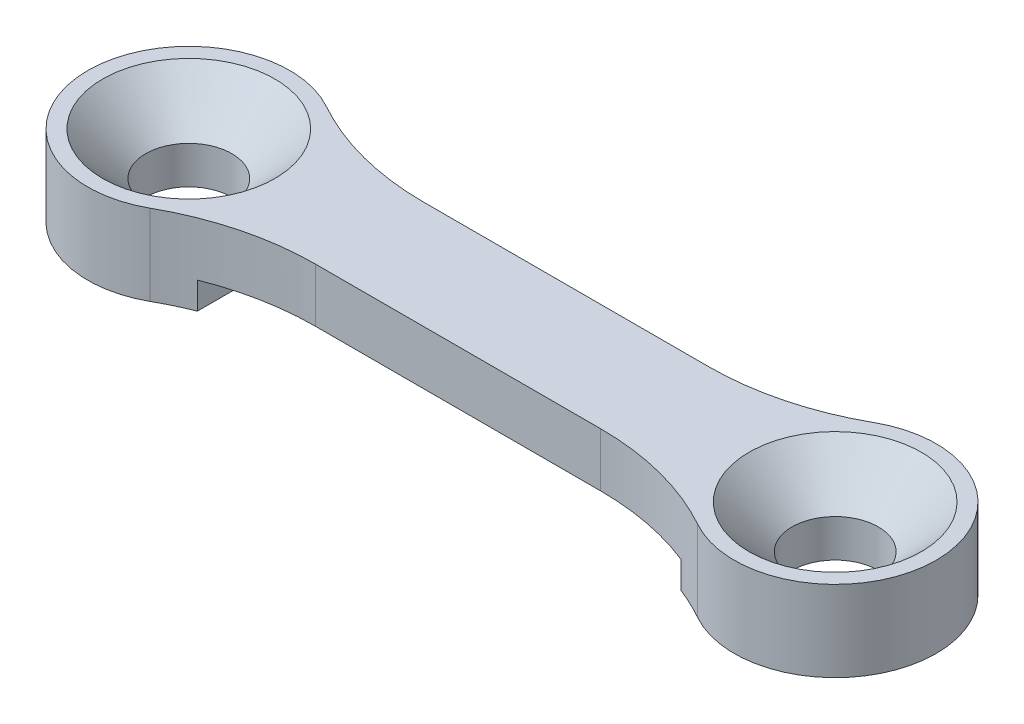
SolidWorks part; units mm, degrees
ref_plane "Front Plane" through (0, 0, 0) normal (0, 0, 1) x (1, 0, 0)
ref_plane "Top Plane" through (0, 0, 0) normal (0, 1, 0) x (1, 0, 0)
ref_plane "Right Plane" through (0, 0, 0) normal (1, 0, 0) x (0, 0, -1)
sketch "Sketch1" plane through (0, 0, 0) normal (0, 1, 0) x (1, 0, 0)
  line L0 (12, 0) -> (-12, 0) construction
  line L1 (-8.8279, 2) -> (8.8279, 2)
  line L2 (-8.8279, -2) -> (8.8279, -2)
  circle A0 centre (-12, 0) radius 1.6
  circle A1 centre (12, 0) radius 1.6
  circle A2 centre (-12, 0) radius 3.75
  circle A3 centre (12, 0) radius 3.75
  point P4 (0, 0)
  dimension "D2" = 3.2
  dimension "D3" = 7.5
  dimension "D1" = 24
  dimension "D4" = 4
extrude "Boss-Extrude1" add sketch "Sketch1" along normal blind 3
chamfer "Chamfer1" distance 1.6 angle 45 2 edges at (12, 3, 1.6) (-12, 3, 1.6)
fillet "Fillet1" radius 10 4 edges at (8.8279, 1.5, 2) (8.8279, 1.5, -2) (-8.8279, 1.5, -2) (-8.8279, 1.5, 2)
sketch "Sketch2" plane through (0, 0, 0) normal (0, -1, 0) x (-1, 0, 0)
  line L1 (-8.975, 2.7049) -> (8.975, 2.7049)
  line L2 (-8.975, 2.7049) -> (-8.975, -2.7049)
  line L3 (-8.975, -2.7049) -> (8.975, -2.7049)
  line L4 (8.975, 2.7049) -> (8.975, -2.7049)
  line L5 (-8.975, 2.7049) -> (8.975, -2.7049) construction
  line L6 (-8.975, -2.7049) -> (8.975, 2.7049) construction
  arc A2 (10.1692, -3.2727) -> (5.2871, -2) centre (5.2871, -12) ccw construction
  point P0 (0, 0)
  dimension "D1" = 17.95
extrude "Cut-Extrude1" cut sketch "Sketch2" against normal blind 1
